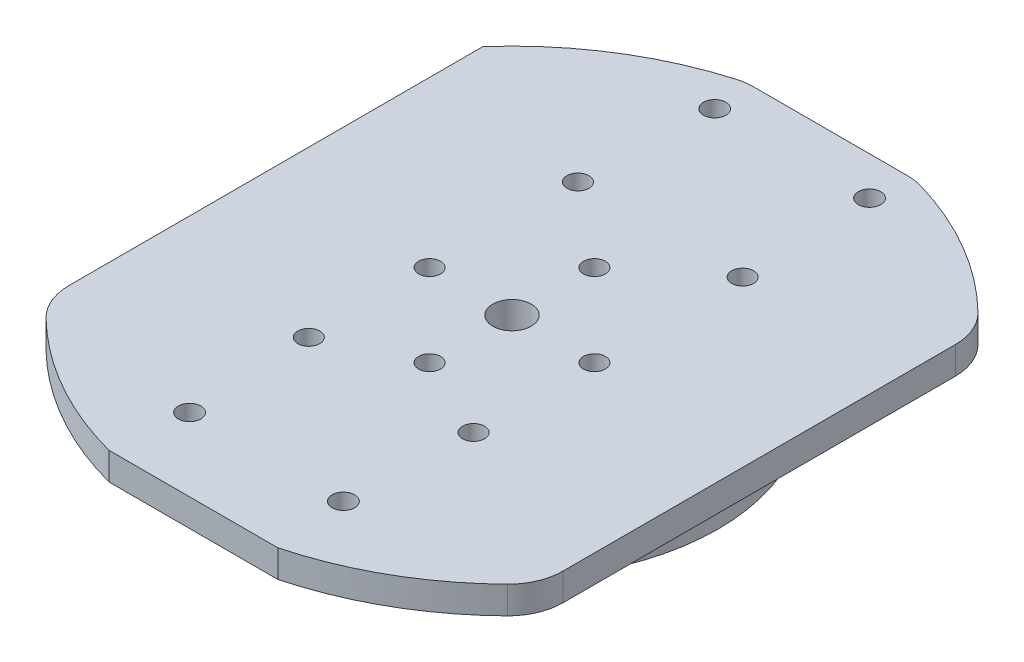
SolidWorks part; units mm, degrees
ref_plane "Front Plane" through (0, 0, 0) normal (0, 0, 1) x (1, 0, 0)
ref_plane "Top Plane" through (0, 0, 0) normal (0, 1, 0) x (1, 0, 0)
ref_plane "Right Plane" through (0, 0, 0) normal (1, 0, 0) x (0, 0, -1)
sketch "Sketch2" plane through (0, 0, 0) normal (0, 1, 0) x (1, 0, 0)
  circle A0 centre (0, 0) radius 6.4
  dimension "D1" = 12.8
extrude "Boss-Extrude1" add sketch "Sketch2" along normal blind 20
sketch "Sketch3" plane through (0, 20, 0) normal (0, 1, 0) x (1, 0, 0)
  circle A0 centre (0, 0) radius 8
  dimension "D1" = 16
extrude "Boss-Extrude2" add sketch "Sketch3" along normal blind 1
sketch "Sketch4" plane through (0, 21, 0) normal (0, 1, 0) x (1, 0, 0)
  circle A0 centre (0, 0) radius 60
  dimension "D1" = 120
extrude "Boss-Extrude3" add sketch "Sketch4" along normal blind 5
sketch "Sketch5" plane through (0, 26, 0) normal (0, 1, 0) x (1, 0, 0)
  circle A0 centre (0, 15) radius 2
  dimension "D1" = 4
  dimension "D2" = 15
extrude "Cut-Extrude1" cut sketch "Sketch5" against normal through all both and the other way through all
pattern_circular "CirPattern1" count 4 over 360 about axis through (0, 0, 0) along (0, 1, 0) of "Cut-Extrude1"
sketch "Sketch6" plane through (0, 26, 0) normal (0, 1, 0) x (1, 0, 0)
  circle A0 centre (0, 0) radius 3.5
  dimension "D1" = 7
extrude "Cut-Extrude2" cut sketch "Sketch6" against normal through all both and the other way through all
sketch "Sketch7" plane through (0, 26, 0) normal (0, 1, 0) x (1, 0, 0)
  circle A0 centre (-14, -44.7) radius 2.05
  circle A1 centre (14, -44.7) radius 2.05
  circle A2 centre (-14.1, 51) radius 2.05
  circle A3 centre (14.1, 51) radius 2.05
extrude "Cut-Extrude3" cut sketch "Sketch7" against normal through all both and the other way through all
sketch "Sketch8" plane through (0, 26, 0) normal (0, 1, 0) x (1, 0, 0)
  line L0 (-15.3623, 58) -> (15.3623, 58)
  circle A0 centre (0, 0) radius 60 construction
  arc A1 (15.3623, 58) -> (-15.3623, 58) centre (0, 0) ccw
  dimension "D1" = 58
extrude "Cut-Extrude4" cut sketch "Sketch8" against normal through all both and the other way through all
mirror "Mirror1" about plane through (0, 0, 0) normal (0, 0, 1) of "Cut-Extrude4"
sketch "Sketch9" plane through (0, 26, 0) normal (0, 1, 0) x (1, 0, 0)
  line L1 (-15.3623, 58) -> (15.3623, 58)
  line L2 (-15.3623, 58) -> (-15.3623, -58)
  line L3 (-15.3623, -58) -> (15.3623, -58)
  line L4 (15.3623, 58) -> (15.3623, -58)
sketch "Sketch10" plane through (0, 0, 0) normal (1, 0, 0) x (0, 0, -1)
  circle A0 centre (0, 8.5) radius 1.5
  dimension "D1" = 3
  dimension "D2" = 8.5
extrude "Cut-Extrude6" cut sketch "Sketch10" against normal through all both and the other way through all
sketch "Sketch13" plane through (0, 0, 0) normal (0, -1, 0) x (1, 0, 0)
  circle A0 centre (0, 0) radius 2.5
  dimension "D1" = 5
sketch "Sketch14" plane through (0, 0, 0) normal (0, -1, 0) x (1, 0, 0)
  circle A0 centre (0, 0) radius 6.4
  circle A1 centre (0, 0) radius 3.5
  dimension "D1" = 12.8
  dimension "D2" = 7
extrude "Cut-Extrude9" cut sketch "Sketch14" against normal blind 4 and the other way through all
sketch "Sketch16" plane through (0, 21, 0) normal (0, -1, 0) x (1, 0, 0)
  circle A0 centre (0, 0) radius 35.05
  circle A1 centre (0, 0) radius 37.5
  dimension "D1" = 70.1
  dimension "D2" = 75
extrude "Boss-Extrude4" add sketch "Sketch16" along normal blind 10
sketch "Sketch18" plane through (0, 26, 0) normal (0, 1, 0) x (1, 0, 0)
  circle A0 centre (0, 0) radius 60
  dimension "D1" = 120
sketch "Sketch19" plane through (0, 26, 0) normal (0, 1, 0) x (1, 0, 0)
  circle A0 centre (-15, 27) radius 2
  circle A1 centre (15, 27) radius 2
  circle A2 centre (15, -22) radius 2
  circle A3 centre (-15, -22) radius 2
  dimension "D1" = 4
  dimension "D2" = 4
  dimension "D3" = 4
  dimension "D4" = 4
extrude "Cut-Extrude10" cut sketch "Sketch19" against normal up to surface (5 mm away) up to face at (0, 21, 37.5)
sketch "Sketch20" plane through (0, 21, 0) normal (0, -1, 0) x (1, 0, 0)
  circle A1 centre (0, 0) radius 35.05 construction
  circle A2 centre (0, 0) radius 33.05
  circle A3 centre (0, 0) radius 33.05
  circle A4 centre (0, 0) radius 35.05
  dimension "D1" = 2
extrude "Boss-Extrude5" add sketch "Sketch20" along normal blind 2
sketch "Sketch21" plane through (0, 21, 0) normal (0, -1, 0) x (1, 0, 0)
  circle A0 centre (0, 0) radius 19
  circle A1 centre (0, 0) radius 22.5
  dimension "D1" = 38
  dimension "D2" = 45
extrude "Boss-Extrude6" add sketch "Sketch21" along normal blind 2
sketch "Sketch22" plane through (0, 26, 0) normal (0, 1, 0) x (1, 0, 0)
  line L0 (-15.3623, -58) -> (15.3623, -58) construction
  line L1 (-45, 58) -> (45, 58)
  line L2 (-45, 58) -> (-45, -58)
  line L3 (-45, -58) -> (45, -58)
  line L4 (45, 58) -> (45, -58)
  line L5 (-45, 58) -> (45, -58) construction
  line L6 (-45, -58) -> (45, 58) construction
  point P0 (0, 0)
  dimension "D1" = 90
extrude "Cut-Extrude11" cut sketch "Sketch22" against normal through all both and the other way through all flip side to cut
fillet "Fillet1" radius 10 5 edges at (15.3623, 23.5, -58) (-15.3623, 23.5, -58) (45, 23.5, 39.6863) (45, 23.5, -39.6863) (-45, 23.5, 39.6863)
